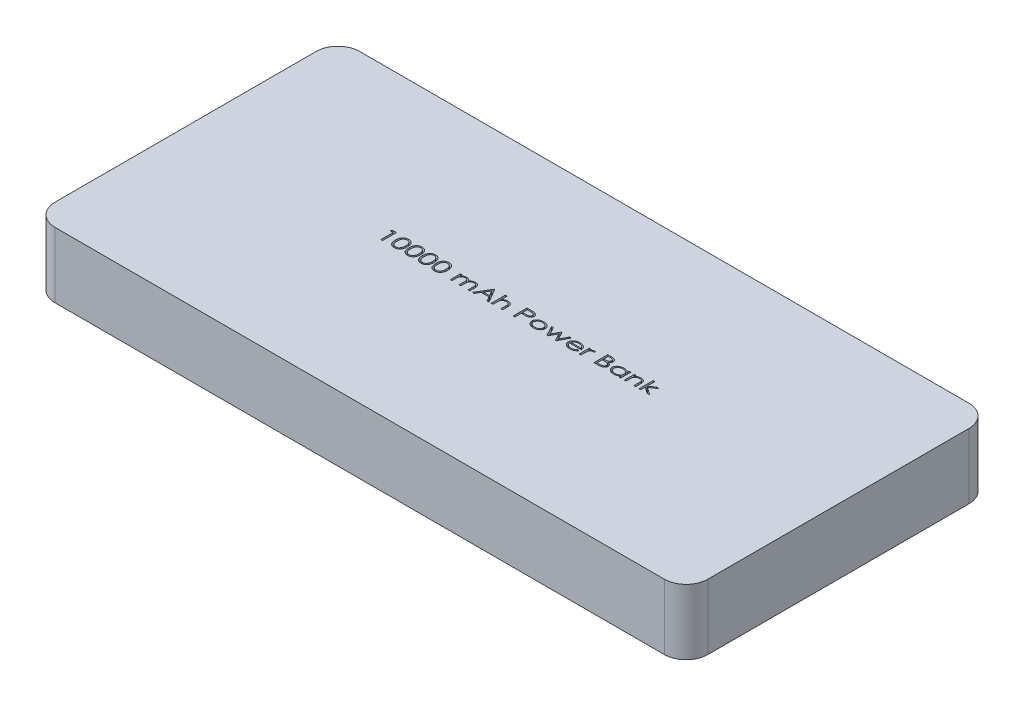
SolidWorks part; units mm, degrees
ref_plane "Front Plane" through (0, 0, 0) normal (0, 0, 1) x (1, 0, 0)
ref_plane "Top Plane" through (0, 0, 0) normal (0, 1, 0) x (1, 0, 0)
ref_plane "Right Plane" through (0, 0, 0) normal (1, 0, 0) x (0, 0, -1)
sketch "Sketch1" plane through (0, 0, 0) normal (0, 1, 0) x (1, 0, 0)
  line L1 (-70, -35) -> (70, -35)
  line L2 (-75, -30) -> (-75, 30)
  line L3 (-70, 35) -> (70, 35)
  line L4 (75, -30) -> (75, 30)
  line L5 (-75, -35) -> (75, 35) construction
  line L6 (-75, 35) -> (75, -35) construction
  arc A0 (70, -35) -> (75, -30) centre (70, -30) ccw
  arc A1 (70, 35) -> (75, 30) centre (70, 30) cw
  arc A2 (-70, -35) -> (-75, -30) centre (-70, -30) cw
  arc A3 (-75, 30) -> (-70, 35) centre (-70, 30) cw
  point P0 (0, 0)
  dimension "D1" = 5
extrude "Boss-Extrude1" add sketch "Sketch1" along normal blind 15
sketch "Sketch2" plane through (0, 15, 0) normal (0, 1, 0) x (1, 0, 0)
  line L0 (-75, 0) -> (75, 0) construction
  line L1 (-75, 30) -> (-75, -30) construction
  line L2 (75, -30) -> (75, 30) construction
  text T0 "10000 mAh Power Bank" font "Century Gothic" height 3.175
extrude "Cut-Extrude1" cut sketch "Sketch2" against normal blind 5
